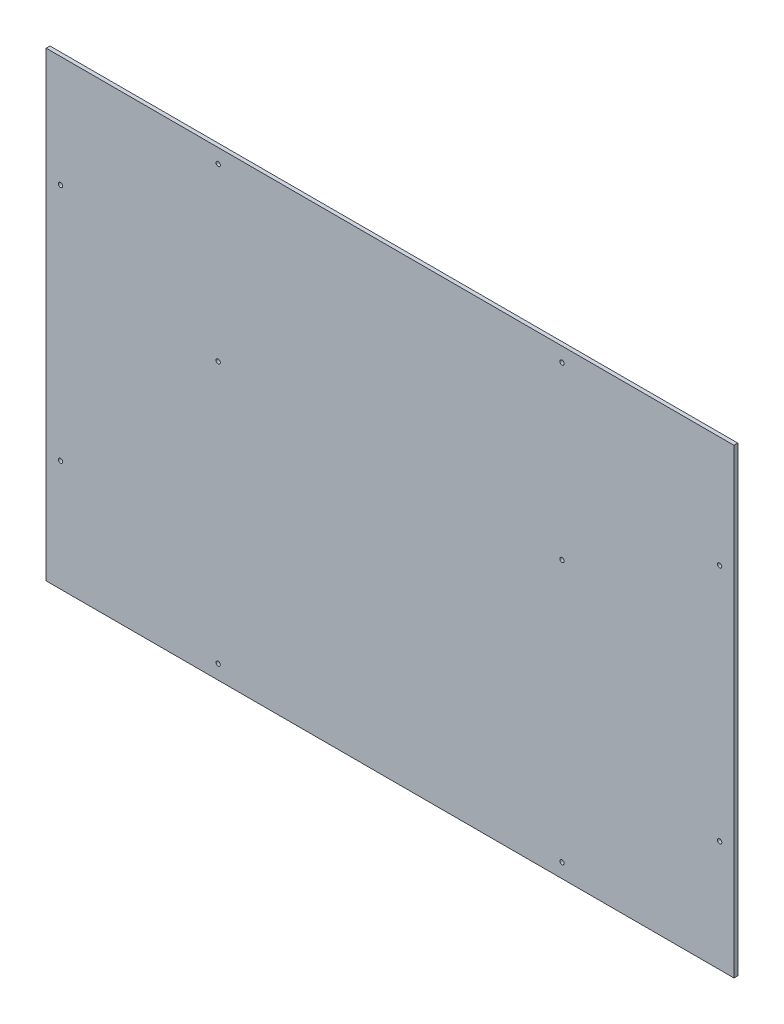
SolidWorks part; units mm, degrees
material "PC"
ref_plane "Front Plane" through (0, 0, 0) normal (0, 0, 1) x (1, 0, 0)
ref_plane "Top Plane" through (0, 0, 0) normal (0, 1, 0) x (1, 0, 0)
ref_plane "Right Plane" through (0, 0, 0) normal (1, 0, 0) x (0, 0, -1)
sketch "Sketch1" plane through (0, 0, 0) normal (0, 0, 1) x (1, 0, 0)
  line L1 (-360, 0) -> (360, 0)
  line L2 (-360, 0) -> (-360, -483)
  line L3 (-360, -483) -> (360, -483)
  line L4 (360, 0) -> (360, -483)
  dimension "D1" = 720
  dimension "D2" = 483
extrude "Boss-Extrude1" add sketch "Sketch1" along normal mid plane 4
sketch "Sketch2" plane through (0, 0, -2) normal (0, 0, -1) x (-1, 0, 0)
  line L0 (0, -15) -> (-180, -15) construction
  line L1 (-360, -116.5) -> (-345, -116.5) construction
  line L3 (-180, -194) -> (0, -194) construction
  line L4 (0, -194) -> (0, -483) construction
  line L5 (360, -483) -> (-360, -483) construction
  line L6 (0, 0) -> (0, -15) construction
  line L7 (-360, 0) -> (360, 0) construction
  line L8 (0, -15) -> (0, -194) construction
  line L9 (-360, 0) -> (360, 0) construction
  line L10 (-360, -483) -> (-360, 0) construction
  line L11 (-360, -366.5) -> (-345, -366.5) construction
  line L12 (-345, -116.5) -> (-345, -366.5) construction
  line L13 (-345, -241.5) -> (-360, -241.5) construction
  line L14 (0, -468) -> (-180, -468) construction
  circle A0 centre (-345, -116.5) radius 2.25
  circle A1 centre (0, -15) radius 2.25 construction
  circle A2 centre (0, -194) radius 2.25 construction
  circle A3 centre (-180, -15) radius 2.25
  circle A4 centre (-180, -194) radius 2.25
  circle A5 centre (180, -194) radius 2.25
  circle A6 centre (345, -116.5) radius 2.25
  circle A7 centre (180, -15) radius 2.25
  circle A8 centre (-345, -366.5) radius 2.25
  circle A9 centre (345, -366.5) radius 2.25
  circle A10 centre (-180, -468) radius 2.25
  circle A11 centre (0, -468) radius 2.25 construction
  circle A12 centre (180, -468) radius 2.25
  dimension "D1" = 4.5
  dimension "D2" = 345
  dimension "D6" = 250
  dimension "D7" = 468
  dimension "D3" = 15
  dimension "D4" = 194
  dimension "D5" = 180
extrude "Cut-Extrude1" cut sketch "Sketch2" against normal through all
